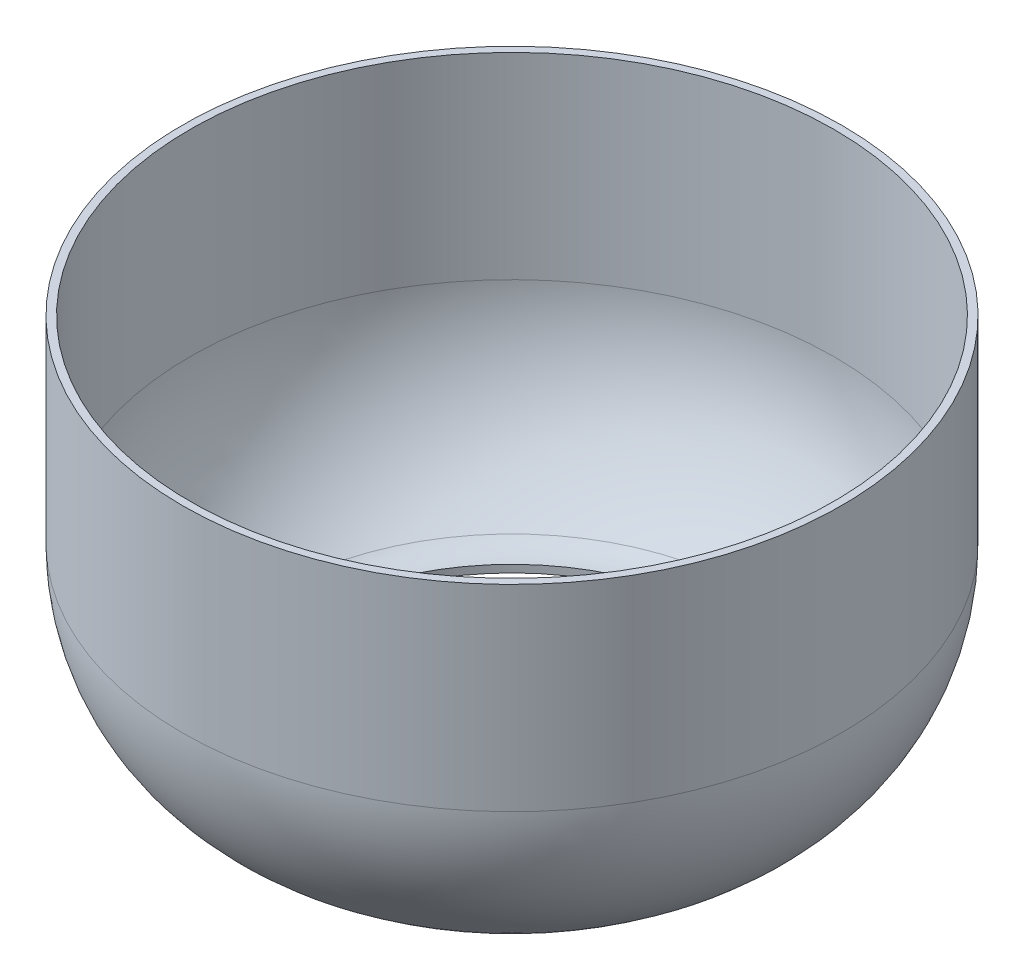
SolidWorks part; units mm, degrees
ref_plane "Ön Düzlem" through (0, 0, 0) normal (0, 0, 1) x (1, 0, 0)
ref_plane "Üst Düzlem" through (0, 0, 0) normal (0, 1, 0) x (1, 0, 0)
ref_plane "Sağ Düzlem" through (0, 0, 0) normal (1, 0, 0) x (0, 0, -1)
sketch "Çizim1" plane through (0, 0, 0) normal (0, 0, 1) x (1, 0, 0)
  line L0 (0, 0) -> (0, 26.469) construction
  line L1 (-64.5, 0) -> (-64.5, 39.42)
  line L2 (-66, 0) -> (-66, 39.42)
  line L3 (-47.5, 0) -> (-47.5, -32.4025) construction
  line L4 (-42.66, -35.42) -> (-42.66, -33.92)
  line L5 (-66, 39.42) -> (-64.5, 39.42)
  arc A0 (-64.5, 0) -> (-47.7299, -32.2424) centre (-25.12, 0) ccw
  arc A1 (-66, 0) -> (-48.6075, -33.4591) centre (-25.12, 0) ccw
  arc A2 (-47.7299, -32.2424) -> (-42.66, -33.92) centre (-42.66, -25.42) ccw
  arc A3 (-48.6075, -33.4591) -> (-42.66, -35.42) centre (-42.66, -25.42) ccw
  arc A4 (-48.6246, -33.4464) -> (-42.66, -35.42) centre (-42.66, -25.42) ccw construction
  arc A5 (-66, 0) -> (-48.3525, -33.6367) centre (-25.12, 0) ccw construction
  arc A6 (-64.5, 0) -> (-47.5, -32.4025) centre (-25.12, 0) ccw construction
  dimension "D2" = 1.5
  dimension "D3" = 1.5
  dimension "D5" = 25.42
  dimension "D1" = 25.12
  dimension "D4" = 42.66
revolve "Döndür1" add sketch "Çizim1" angle 360 about L0
